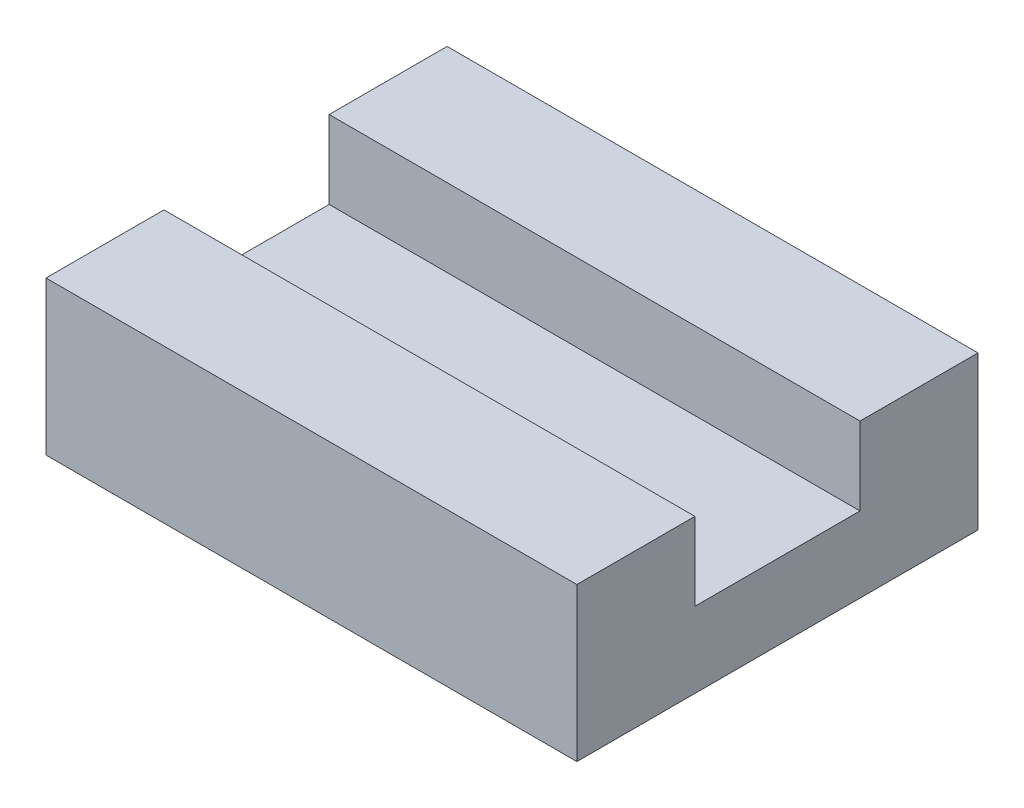
SolidWorks part; units mm, degrees
ref_plane "前视基准面" through (0, 0, 0) normal (0, 0, 1) x (1, 0, 0)
ref_plane "上视基准面" through (0, 0, 0) normal (0, 1, 0) x (1, 0, 0)
ref_plane "右视基准面" through (0, 0, 0) normal (1, 0, 0) x (0, 0, -1)
ref_plane "基准面4" through (-11.25, 0, 0) normal (-1, 0, 0) x (0, -1, 0)
sketch "草图1" plane through (-11.25, 0, 0) normal (-1, 0, 0) x (0, -1, 0)
  line L0 (-6.5, 3.5) -> (-3.2, 3.5)
  line L1 (-3.2, 3.5) -> (-3.2, -3.5)
  line L2 (-3.2, -3.5) -> (-6.5, -3.5)
  line L3 (-6.5, -3.5) -> (-6.5, -8.5)
  line L4 (-6.5, -8.5) -> (0, -8.5)
  line L5 (0, -8.5) -> (0, 8.5)
  line L6 (0, 8.5) -> (-6.5, 8.5)
  line L7 (-6.5, 8.5) -> (-6.5, 3.5)
extrude "凸台-拉伸1" add sketch "草图1" against normal blind 22.5
